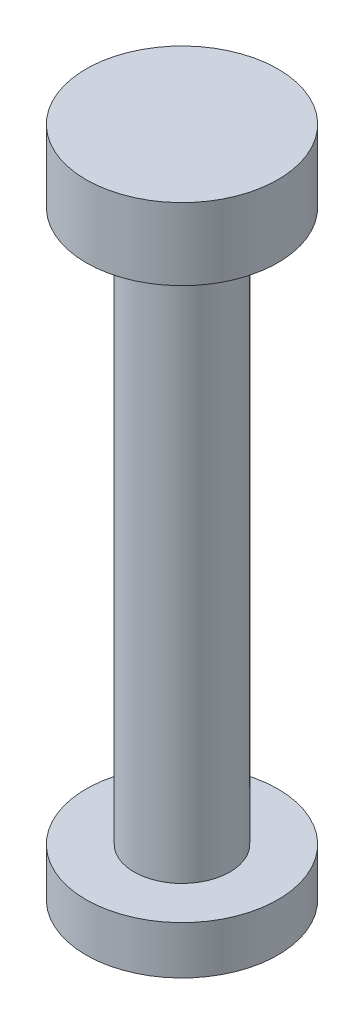
SolidWorks part; units mm, degrees
ref_plane "Front Plane" through (0, 0, 0) normal (0, 0, 1) x (1, 0, 0)
ref_plane "Top Plane" through (0, 0, 0) normal (0, 1, 0) x (1, 0, 0)
ref_plane "Right Plane" through (0, 0, 0) normal (1, 0, 0) x (0, 0, -1)
sketch "Sketch1" plane through (0, 0, 0) normal (0, 0, 1) x (1, 0, 0)
  line L0 (0, 0) -> (0, 26.12) construction
  line L1 (0, 26) -> (4, 26)
  line L2 (4, 26) -> (4, 23)
  line L3 (4, 23) -> (2, 23)
  line L4 (2, 23) -> (2, 0)
  line L5 (2, 0) -> (4, 0)
  line L6 (4, 0) -> (4, -2)
  line L7 (4, -2) -> (0, -2)
  line L8 (0, -2) -> (0, 26)
  point P6 (3, 0)
  dimension "D1" = 23
  dimension "D2" = 4
  dimension "D3" = 2
  dimension "D4" = 4
  dimension "D5" = 2
  dimension "D6" = 3
revolve "Revolve1" add sketch "Sketch1" angle 360 about L0
